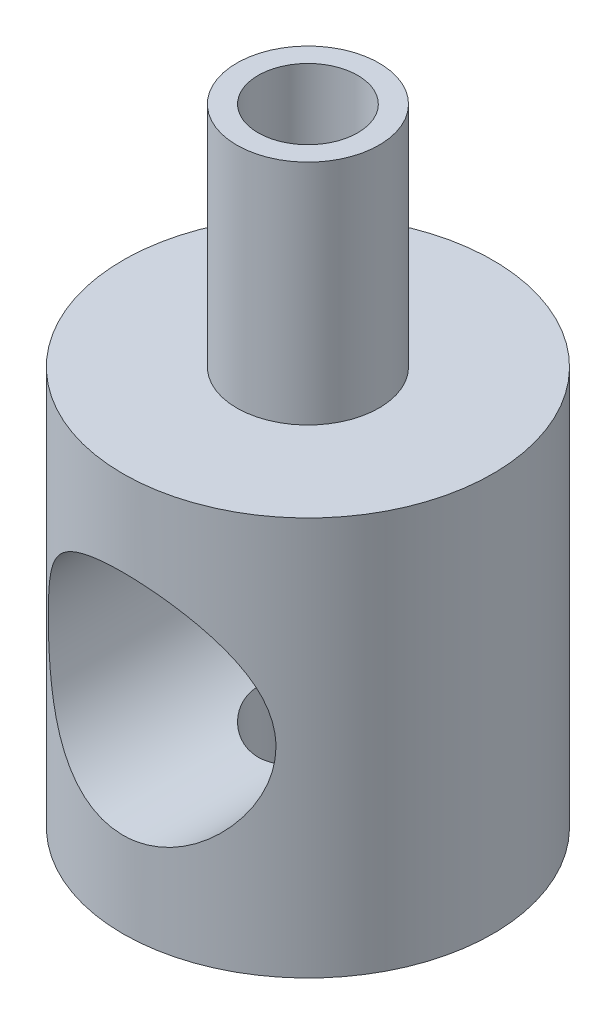
SolidWorks part; units mm, degrees
ref_plane "Front Plane" through (0, 0, 0) normal (0, 0, 1) x (1, 0, 0)
ref_plane "Top Plane" through (0, 0, 0) normal (0, 1, 0) x (1, 0, 0)
ref_plane "Right Plane" through (0, 0, 0) normal (1, 0, 0) x (0, 0, -1)
sketch "Sketch1" plane through (0, 0, 0) normal (0, 1, 0) x (1, 0, 0)
  circle A0 centre (0, 0) radius 6.5
  dimension "D1" = 13
extrude "Boss-Extrude1" add sketch "Sketch1" along normal blind 14
sketch "Sketch2" plane through (0, 14, 0) normal (0, 1, 0) x (1, 0, 0)
  circle A0 centre (0, 0) radius 2.5
  dimension "D1" = 5
extrude "Boss-Extrude2" add sketch "Sketch2" along normal blind 8
sketch "Sketch3" plane through (0, 0, 0) normal (0, 0, 1) x (1, 0, 0)
  line L0 (-6.5, 14) -> (-6.5, 0) construction
  circle A0 centre (0, 7) radius 4
  dimension "D1" = 8
  dimension "D2" = 7
  dimension "D3" = 6.5
extrude "Cut-Extrude1" cut sketch "Sketch3" against normal through all both and the other way through all
sketch "Sketch4" plane through (0, 22, 0) normal (0, 1, 0) x (1, 0, 0)
  circle A0 centre (0, 0) radius 1.75
  dimension "D1" = 3.5
extrude "Cut-Extrude2" cut sketch "Sketch4" against normal through all
